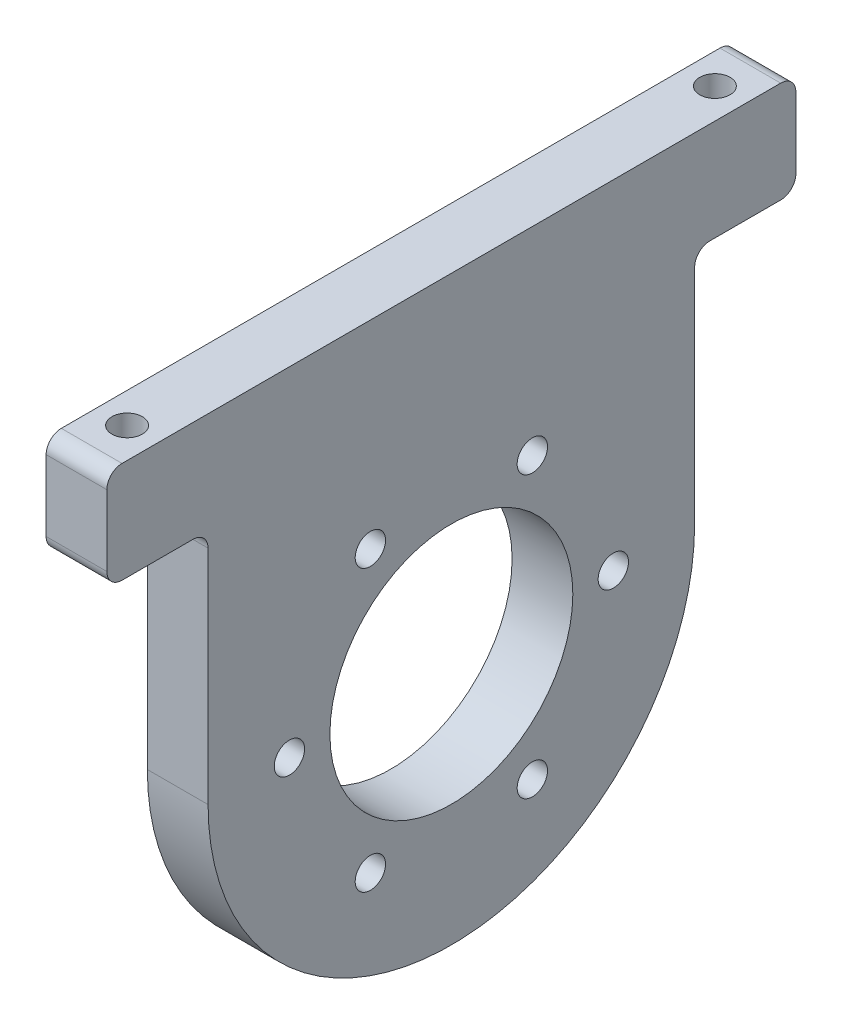
SolidWorks part; units mm, degrees
material "6061 Alloy"
ref_plane "Front Plane" through (0, 0, 0) normal (0, 0, 1) x (1, 0, 0)
ref_plane "Top Plane" through (0, 0, 0) normal (0, 1, 0) x (1, 0, 0)
ref_plane "Right Plane" through (0, 0, 0) normal (1, 0, 0) x (0, 0, -1)
sketch "Sketch1" plane through (0, 0, 0) normal (1, 0, 0) x (0, 0, -1)
  line L0 (0, 0) -> (0, -10)
  line L1 (0, -10) -> (10, -10)
  line L2 (10, -10) -> (10, -33.4393)
  line L3 (58.0694, -33.4393) -> (58.0694, -10)
  line L4 (58.0694, -10) -> (68.0694, -10)
  line L5 (68.0694, -10) -> (68.0694, 0)
  line L6 (0, 0) -> (68.0694, 0)
  line L7 (15.0347, -22.4697) -> (15.0347, -44.409) construction
  line L8 (15.0347, -44.409) -> (34.0347, -55.3786) construction
  line L9 (34.0347, -55.3786) -> (53.0347, -44.409) construction
  line L10 (53.0347, -44.409) -> (53.0347, -22.4697) construction
  line L11 (53.0347, -22.4697) -> (34.0347, -11.5) construction
  line L12 (34.0347, -11.5) -> (15.0347, -22.4697) construction
  circle A0 centre (34.0347, -33.4393) radius 24.0347
  circle A1 centre (34.0347, -33.4393) radius 19 construction
  circle A2 centre (34.0347, -33.4393) radius 21.5347
  circle A3 centre (34.0347, -33.4393) radius 12
  dimension "D1" = 48.0694
  dimension "D6" = 43.0694
  dimension "D7" = 24
  dimension "D2" = 10
  dimension "D3" = 10
  dimension "D4" = 1.5
  dimension "D5" = 38
extrude "Boss-Extrude1" add sketch "Sketch1" along normal blind 6 contours A0 L3 L4 L5 L6 L0 L1 L2 | A0 | A2
sketch "Sketch2" plane through (0, 0, 0) normal (0, 1, 0) x (1, 0, 0)
  line L0 (0, 0) -> (6, 10)
  line L1 (6, 0) -> (6, 68.0694) construction
  line L2 (6, 34.0347) -> (0, 34.0347)
  line L3 (0, 0) -> (0, 68.0694) construction
  circle A0 centre (3, 5) radius 1.5
  circle A1 centre (3, 63.0694) radius 1.5
  dimension "D1" = 3
extrude "Cut-Extrude1" cut sketch "Sketch2" against normal up to surface (10 mm away) contours A1 | L0 A0 | L0 A0
sketch "Sketch3" plane through (0, 0, 0) normal (1, 0, 0) x (0, 0, -1)
  circle A2 centre (42.0347, -47.2957) radius 1.5
  circle A3 centre (42.0347, -47.2957) radius 1.5
  circle A10 centre (50.0347, -33.4393) radius 1.5
  circle A11 centre (50.0347, -33.4393) radius 1.5
  circle A13 centre (26.0347, -19.5829) radius 1.5
  circle A14 centre (26.0347, -19.5829) radius 1.5
  circle A16 centre (18.0347, -33.4393) radius 1.5
  circle A17 centre (18.0347, -33.4393) radius 1.5
  circle A19 centre (42.0347, -19.5829) radius 1.5
  circle A20 centre (42.0347, -19.5829) radius 1.5
  circle A22 centre (26.0347, -47.2957) radius 1.5
  circle A23 centre (26.0347, -47.2957) radius 1.5
  dimension "D1" = 0.25
  dimension "D2" = 0.25
  dimension "D3" = 0.25
  dimension "D4" = 0.25
  dimension "D5" = 0.25
  dimension "D6" = 0.25
extrude "Cut-Extrude2" cut sketch "Sketch3" along normal up to surface (6 mm away)
fillet "Fillet1" radius 1.5
